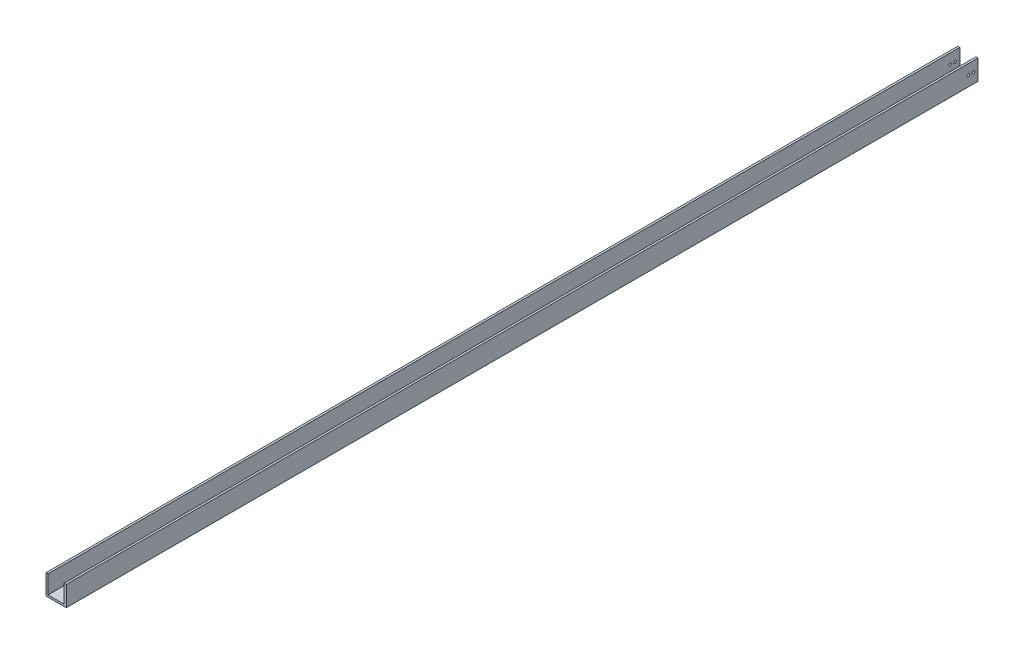
SolidWorks part; units mm, degrees
material "6061-T6 (SS)"
ref_plane "Front" through (0, 0, 0) normal (0, 0, 1) x (1, 0, 0)
ref_plane "Top" through (0, 0, 0) normal (0, 1, 0) x (1, 0, 0)
ref_plane "Right" through (0, 0, 0) normal (1, 0, 0) x (0, 0, -1)
sketch "Croquis1" plane through (0, 0, 0) normal (0, 0, 1) x (1, 0, 0)
  line L0 (0, 0) -> (4, 0)
  line L1 (4, -36) -> (36, -36)
  line L2 (36, -36) -> (36, 0)
  line L3 (36, 0) -> (40, 0)
  line L4 (40, 0) -> (40, -40)
  line L5 (40, -40) -> (0, -40)
  line L6 (0, -40) -> (0, 0)
  line L7 (4, 0) -> (4, -36)
  dimension "D1" = 40
  dimension "D2" = 40
  dimension "D3" = 4
  dimension "D4" = 4
extrude "Saliente-Extruir1" add sketch "Croquis1" along normal blind 1800
sketch "Croquis2" plane through (0, 0, 0) normal (-1, 0, 0) x (0, 0, 1)
  line L0 (0, 0) -> (0, -40) construction
  line L1 (0, -20) -> (9, -20) construction
  circle A0 centre (9, -20) radius 2.5
  circle A1 centre (19, -20) radius 2.5
  dimension "D1" = 10
  dimension "5" = 5
  dimension "D2" = 9
extrude "Cortar-Extruir1" cut sketch "Croquis2" against normal through all
sketch "Croquis3" plane through (0, -40, 0) normal (0, -1, 0) x (-1, 0, 0)
  line L0 (0, 0) -> (-40, 0) construction
  line L1 (-20, 0) -> (-20, -19) construction
  circle A0 centre (-20, -9) radius 2.5
  circle A1 centre (-20, -19) radius 2.5
  dimension "D1" = 9
  dimension "D2" = 10
  dimension "D3" = 5
extrude "Cortar-Extruir2" cut sketch "Croquis3" against normal blind 10
